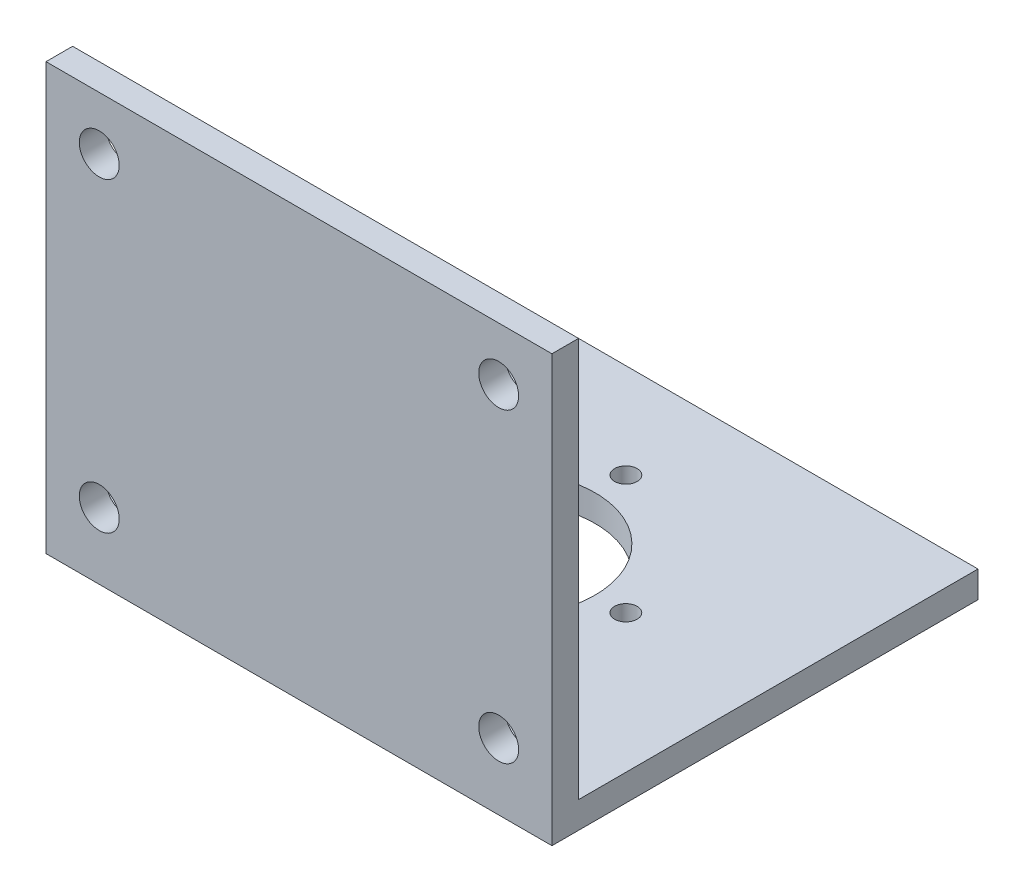
SolidWorks part; units mm, degrees
ref_plane "前视基准面" through (0, 0, 0) normal (0, 0, 1) x (1, 0, 0)
ref_plane "上视基准面" through (0, 0, 0) normal (0, 1, 0) x (1, 0, 0)
ref_plane "右视基准面" through (0, 0, 0) normal (1, 0, 0) x (0, 0, -1)
sketch "草图3" plane through (0, 0, 0) normal (0, 0, 1) x (1, 0, 0)
  line L0 (19, -32.8332) -> (19, 32.8332) construction
  line L1 (0, 0) -> (38, 0)
  line L2 (0, 0) -> (0, 32)
  line L3 (0, 32) -> (38, 32)
  line L4 (38, 0) -> (38, 32)
  line L5 (19, 0) -> (19, 5)
  line L6 (19, 5) -> (4, 5)
  line L7 (19, 5) -> (34, 5)
  line L8 (4, 5) -> (4, 28)
  line L9 (34, 5) -> (34, 28)
  circle A0 centre (4, 28) radius 1.5
  circle A1 centre (34, 28) radius 1.5
  circle A2 centre (4, 5) radius 1.5
  circle A3 centre (34, 5) radius 1.5
  point P8 (19, 0)
extrude "连板" add sketch "草图3" along normal blind 2 contours L3 L4 L1 L2
sketch "草图4" plane through (0, 0, 0) normal (0, 1, 0) x (1, 0, 0)
  line L1 (0, -2) -> (38, -2)
  line L2 (0, -2) -> (0, 30)
  line L3 (0, 30) -> (38, 30)
  line L4 (38, -2) -> (38, 30)
extrude "连轮" add sketch "草图4" along normal blind 2
sketch "草图5" plane through (0, 0, 0) normal (0, 0, 1) x (1, 0, 0)
  line L0 (19, -33.3598) -> (19, 33.3598) construction
  line L2 (19, 0) -> (19, 5)
  line L3 (19, 5) -> (4, 5)
  line L4 (19, 5) -> (34, 5)
  line L5 (4, 5) -> (4, 28)
  line L6 (34, 5) -> (34, 28)
  circle A0 centre (4, 5) radius 1.5
  circle A1 centre (4, 28) radius 1.5
  circle A2 centre (34, 5) radius 1.5
  circle A3 centre (34, 28) radius 1.5
  point P3 (19, 0)
extrude "切除-拉伸1" cut sketch "草图5" against normal through all both and the other way through all contours A1 | A3 | A2 | A0
sketch "草图6" plane through (0, 0, 0) normal (0, 1, 0) x (1, 0, 0)
  line L0 (18.6648, -35.5304) -> (18.6648, 30.8601) construction
  line L1 (4.736, 27.8577) -> (32.5937, 0)
  line L3 (0, 0) -> (38, 0) construction
  line L8 (32.5937, 27.8577) -> (4.736, 0)
  line L9 (18.6648, 13.9288) -> (9.7048, 13.9288)
  line L10 (18.6648, 13.9288) -> (27.6248, 13.9288)
  line L11 (18.6648, 13.9288) -> (18.6648, 22.8888)
  line L12 (18.6648, 13.9288) -> (18.6648, 4.9688)
  line L13 (7.4008, 2.6648) -> (29.9288, 2.6648)
  line L14 (7.4008, 2.6648) -> (7.4008, 25.1928)
  line L15 (7.4008, 25.1928) -> (29.9288, 25.1928)
  line L16 (29.9288, 2.6648) -> (29.9288, 25.1928)
  line L17 (18.6648, 25.1928) -> (18.6648, 2.6648) construction
  line L18 (7.4008, 13.9288) -> (29.9288, 13.9288) construction
  circle A0 centre (18.6648, 13.9288) radius 6.656
  circle A1 centre (9.7048, 13.9288) radius 0.8448
  circle A2 centre (18.6648, 22.8888) radius 0.8448
  circle A3 centre (27.6248, 13.9288) radius 0.8448
  circle A4 centre (18.6648, 4.9688) radius 0.8448
  point P3 (18.6648, -2.3352)
  point P22 (0, 0)
extrude "切除-拉伸2" cut sketch "草图6" against normal through all and the other way through all contours A2 | A1 | A3 | A4 | A0
